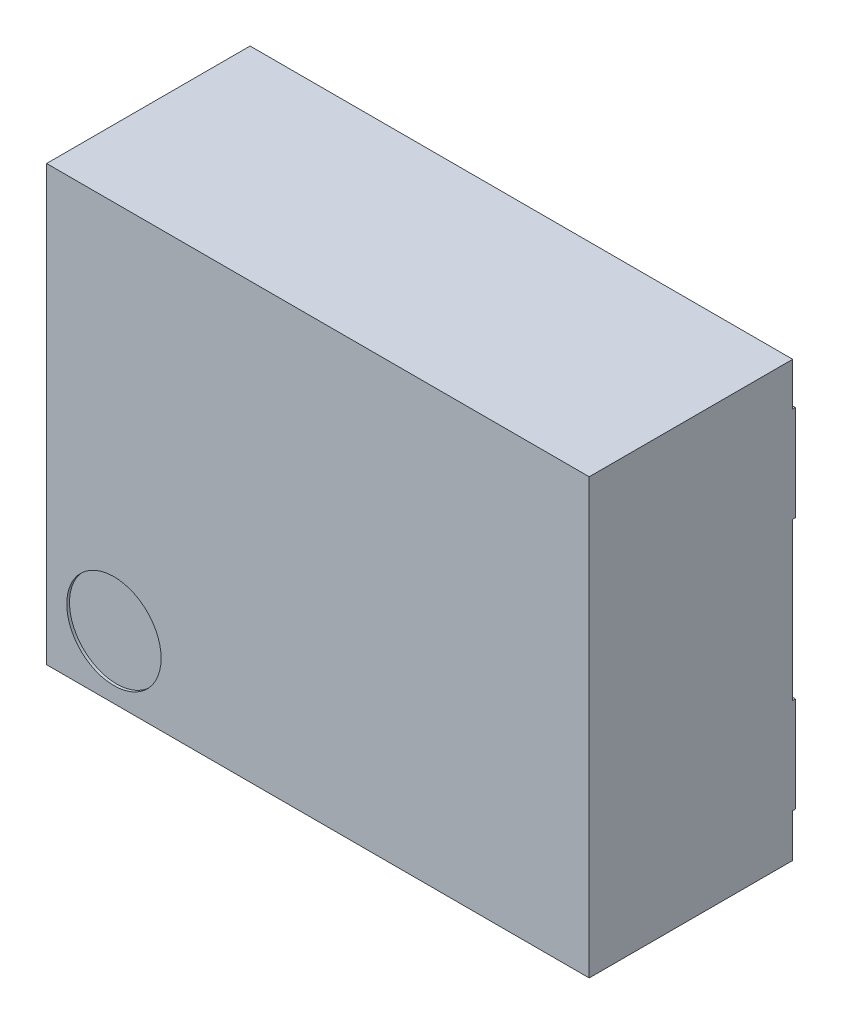
SolidWorks part; units mm, degrees
ref_plane "Front Plane" through (0, 0, 0) normal (0, 0, 1) x (1, 0, 0)
ref_plane "Top Plane" through (0, 0, 0) normal (0, 1, 0) x (1, 0, 0)
ref_plane "Right Plane" through (0, 0, 0) normal (1, 0, 0) x (0, 0, -1)
sketch "Sketch1" plane through (0, 0, 0) normal (0, 0, 1) x (1, 0, 0)
  line L1 (-1, 0.8) -> (1, 0.8)
  line L2 (-1, 0.8) -> (-1, -0.8)
  line L3 (-1, -0.8) -> (1, -0.8)
  line L4 (1, 0.8) -> (1, -0.8)
  line L5 (-1, 0.8) -> (1, -0.8) construction
  line L6 (-1, -0.8) -> (1, 0.8) construction
  point P0 (0, 0)
  dimension "D1" = 2
  dimension "D2" = 1.6
extrude "Boss-Extrude1" add sketch "Sketch1" along normal blind 0.75 contours L1 L4 L3 L2
sketch "Sketch2" plane through (0, 0, 0) normal (0, 0, 1) x (1, 0, 0)
  line L0 (1, 0.641) -> (0.8999, 0.641)
  line L1 (1, 0.8) -> (1, -0.8) construction
  line L2 (0.8999, 0.641) -> (0.8999, 0.655)
  line L3 (0.8499, 0.705) -> (0.37, 0.705)
  line L4 (0.32, 0.655) -> (0.32, 0.275)
  line L5 (0.37, 0.225) -> (0.8499, 0.225)
  line L6 (0.8999, 0.275) -> (0.8999, 0.289)
  line L7 (0.8999, 0.289) -> (1, 0.289)
  line L8 (1, 0.289) -> (1, 0.641)
  line L9 (1, 0.465) -> (0.32, 0.465) construction
  line L10 (0, 0) -> (1, 0) construction
  line L11 (1, -0.465) -> (0.32, -0.465) construction
  line L12 (1, -0.289) -> (1, -0.641)
  line L13 (0.8999, -0.289) -> (1, -0.289)
  line L14 (0.8999, -0.275) -> (0.8999, -0.289)
  line L15 (0.37, -0.225) -> (0.8499, -0.225)
  line L16 (0.32, -0.655) -> (0.32, -0.275)
  line L17 (0.8499, -0.705) -> (0.37, -0.705)
  line L18 (0.8999, -0.641) -> (0.8999, -0.655)
  line L19 (1, -0.641) -> (0.8999, -0.641)
  line L20 (0, 0) -> (0, 0.8) construction
  line L21 (-1, 0.8) -> (1, 0.8) construction
  line L22 (-1, -0.465) -> (-0.32, -0.465) construction
  line L23 (-1, 0.465) -> (-0.32, 0.465) construction
  line L24 (-1, -0.641) -> (-0.8999, -0.641)
  line L25 (-0.8999, -0.641) -> (-0.8999, -0.655)
  line L26 (-0.8499, -0.705) -> (-0.37, -0.705)
  line L27 (-0.32, -0.655) -> (-0.32, -0.275)
  line L28 (-0.37, -0.225) -> (-0.8499, -0.225)
  line L29 (-0.8999, -0.275) -> (-0.8999, -0.289)
  line L30 (-0.8999, -0.289) -> (-1, -0.289)
  line L31 (-1, -0.289) -> (-1, -0.641)
  line L32 (-1, 0.289) -> (-1, 0.641)
  line L33 (-0.8999, 0.289) -> (-1, 0.289)
  line L34 (-0.8999, 0.275) -> (-0.8999, 0.289)
  line L35 (-0.37, 0.225) -> (-0.8499, 0.225)
  line L36 (-0.32, 0.655) -> (-0.32, 0.275)
  line L37 (-0.8499, 0.705) -> (-0.37, 0.705)
  line L38 (-0.8999, 0.641) -> (-0.8999, 0.655)
  line L39 (-1, 0.641) -> (-0.8999, 0.641)
  arc A0 (0.8499, 0.225) -> (0.8999, 0.275) centre (0.8499, 0.275) ccw
  arc A1 (0.8999, 0.655) -> (0.8499, 0.705) centre (0.8499, 0.655) ccw
  arc A2 (0.32, 0.275) -> (0.37, 0.225) centre (0.37, 0.275) ccw
  arc A3 (0.37, 0.705) -> (0.32, 0.655) centre (0.37, 0.655) ccw
  arc A4 (0.37, -0.705) -> (0.32, -0.655) centre (0.37, -0.655) cw
  arc A5 (0.32, -0.275) -> (0.37, -0.225) centre (0.37, -0.275) cw
  arc A6 (0.8999, -0.655) -> (0.8499, -0.705) centre (0.8499, -0.655) cw
  arc A7 (0.8499, -0.225) -> (0.8999, -0.275) centre (0.8499, -0.275) cw
  arc A8 (-0.8499, -0.225) -> (-0.8999, -0.275) centre (-0.8499, -0.275) ccw
  arc A9 (-0.8999, -0.655) -> (-0.8499, -0.705) centre (-0.8499, -0.655) ccw
  arc A10 (-0.32, -0.275) -> (-0.37, -0.225) centre (-0.37, -0.275) ccw
  arc A11 (-0.37, -0.705) -> (-0.32, -0.655) centre (-0.37, -0.655) ccw
  arc A12 (-0.37, 0.705) -> (-0.32, 0.655) centre (-0.37, 0.655) cw
  arc A13 (-0.32, 0.275) -> (-0.37, 0.225) centre (-0.37, 0.275) cw
  arc A14 (-0.8999, 0.655) -> (-0.8499, 0.705) centre (-0.8499, 0.655) cw
  arc A15 (-0.8499, 0.225) -> (-0.8999, 0.275) centre (-0.8499, 0.275) cw
  point P7 (1, 0.465)
  point P20 (0.32, 0.225)
  point P23 (0.32, 0.705)
  point P44 (0.32, -0.705)
  point P45 (0.32, -0.225)
  point P85 (-0.32, -0.225)
  point P86 (-0.32, -0.705)
  point P87 (-0.32, 0.705)
  point P88 (-0.32, 0.225)
  dimension "D4" = 0.05
  dimension "D1" = 0.68
  dimension "D2" = 0.465
  dimension "D3" = 0.48
extrude "Boss-Extrude2" add sketch "Sketch2" against normal blind 0.01 contours A7 L15 A5 L16 A4 L17 A6 L18 L19 L12 L13 L14 | A15 L35 A13 L36 A12 L37 A14 L38 L39 L32 L33 L34 | L26 A11 L27 A10 L28 A8 L29 L30 L31 L24 L25 A9 | L3 A3 L4 A2 L5 A0 L6 L7 L8 L0 L2 A1
sketch "Sketch3" plane through (0, 0, -0.01) normal (0, 0, -1) x (-1, 0, 0)
  line L0 (0.2595, -0.5304) -> (0.6739, -0.116)
  line L1 (0.6739, -0.116) -> (0.2595, -0.116)
  line L2 (0.2595, -0.116) -> (0.2595, -0.5304)
extrude "Cut-Extrude1" cut sketch "Sketch3" against normal up to surface (0.01 mm away) up to face at (0, 0, 0)
sketch "Sketch4" plane through (0, 0, 0.75) normal (0, 0, 1) x (1, 0, 0)
  circle A0 centre (-0.7518, -0.5687) radius 0.1739
extrude "Cut-Extrude2" cut sketch "Sketch4" against normal blind 0.01
